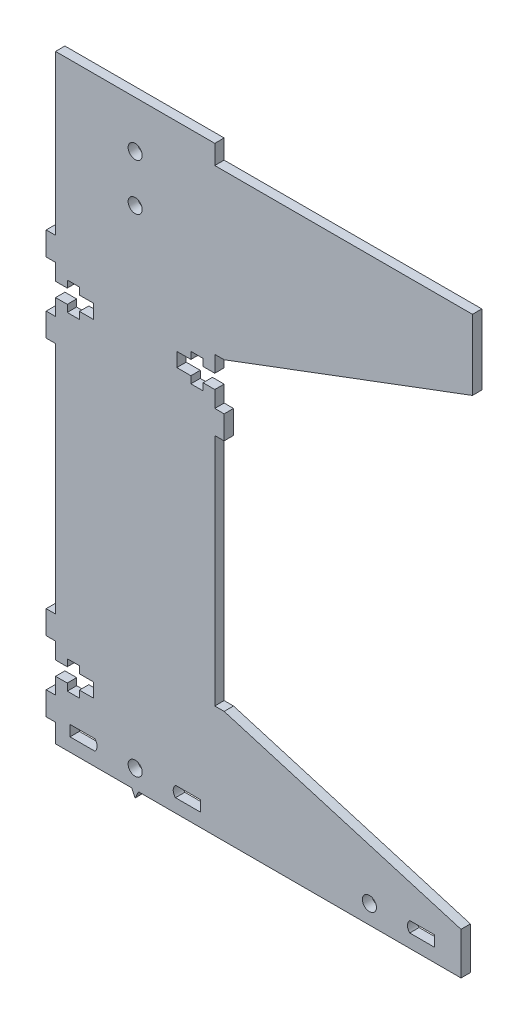
SolidWorks part; units mm, degrees
ref_plane "前视基准面" through (0, 0, 0) normal (0, 0, 1) x (1, 0, 0)
ref_plane "上视基准面" through (0, 0, 0) normal (0, 1, 0) x (1, 0, 0)
ref_plane "右视基准面" through (0, 0, 0) normal (1, 0, 0) x (0, 0, -1)
sketch "草图1" plane through (0, 0, 0) normal (0, 0, 1) x (1, 0, 0)
  line L26 (13.9, -105.15) -> (8.6, -105.15)
  line L27 (13.9, -102.85) -> (13.9, -105.15)
  line L34 (13.9, -102.85) -> (8.6, -102.85)
  line L35 (16.9939, 15.9) -> (16.9939, 20)
  line L36 (71.9939, 15.9) -> (16.9939, 15.9)
  line L37 (71.9939, 0.9) -> (71.9939, 15.9)
  line L40 (18.9939, -34) -> (16.9939, -34)
  line L41 (18.9939, -29) -> (16.9939, -29)
  line L42 (18.9939, -34) -> (18.9939, -29)
  line L47 (16.9939, -22.5) -> (16.9939, -19)
  line L64 (0, -108) -> (0, -109.5)
  line L77 (-13.9, -102.85) -> (-8.6, -102.85)
  line L78 (-13.9, -102.85) -> (-13.9, -105.15)
  line L79 (-13.9, -105.15) -> (-8.6, -105.15)
  line L94 (0, -109.5) -> (0.7212, -108)
  line L95 (0.7212, -108) -> (16.9939, -108)
  line L96 (-0.7212, -108) -> (-16.9939, -108)
  line L97 (0, -109.5) -> (-0.7212, -108)
  line L124 (16.9939, -25.5) -> (16.9939, -29)
  line L126 (14.4939, -25.5) -> (16.9939, -25.5)
  line L127 (14.4939, -21) -> (11.8939, -21)
  line L128 (11.8939, -21) -> (11.8939, -22.5)
  line L129 (11.8939, -22.5) -> (8.8939, -22.5)
  line L130 (11.8939, -25.5) -> (8.8939, -25.5)
  line L131 (11.8939, -27) -> (11.8939, -25.5)
  line L132 (14.4939, -27) -> (11.8939, -27)
  line L133 (16.9939, -22.5) -> (14.4939, -22.5)
  line L134 (14.4939, -22.5) -> (14.4939, -21)
  line L135 (8.8939, -22.5) -> (8.8939, -25.5)
  line L136 (14.4939, -25.5) -> (14.4939, -27)
  line L138 (-18.9939, -104) -> (-18.9939, -99)
  line L139 (-18.9939, -99) -> (-16.9939, -99)
  line L140 (-18.9939, -104) -> (-16.9939, -104)
  line L141 (-14.4939, -95.5) -> (-14.4939, -97)
  line L142 (-8.8939, -92.5) -> (-8.8939, -95.5)
  line L143 (-14.4939, -92.5) -> (-14.4939, -91)
  line L144 (-16.9939, -92.5) -> (-14.4939, -92.5)
  line L145 (-14.4939, -97) -> (-11.8939, -97)
  line L146 (-11.8939, -97) -> (-11.8939, -95.5)
  line L147 (-11.8939, -95.5) -> (-8.8939, -95.5)
  line L148 (-11.8939, -92.5) -> (-8.8939, -92.5)
  line L149 (-11.8939, -91) -> (-11.8939, -92.5)
  line L150 (-14.4939, -91) -> (-11.8939, -91)
  line L151 (-14.4939, -95.5) -> (-16.9939, -95.5)
  line L152 (-16.9939, -89) -> (-16.9939, -92.5)
  line L153 (-16.9939, -95.5) -> (-16.9939, -99)
  line L154 (-16.9939, -89) -> (-18.9939, -89)
  line L155 (-18.9939, -89) -> (-18.9939, -84)
  line L156 (-18.9939, -84) -> (-16.9939, -84)
  line L158 (-16.9939, -104) -> (-16.9939, -108)
  line L179 (-14.4939, -25.5) -> (-14.4939, -27)
  line L180 (-8.8939, -22.5) -> (-8.8939, -25.5)
  line L181 (-14.4939, -22.5) -> (-14.4939, -21)
  line L182 (-16.9939, -22.5) -> (-14.4939, -22.5)
  line L183 (-14.4939, -27) -> (-11.8939, -27)
  line L184 (-11.8939, -27) -> (-11.8939, -25.5)
  line L185 (-11.8939, -25.5) -> (-8.8939, -25.5)
  line L186 (-11.8939, -22.5) -> (-8.8939, -22.5)
  line L187 (-11.8939, -21) -> (-11.8939, -22.5)
  line L188 (-14.4939, -21) -> (-11.8939, -21)
  line L189 (-14.4939, -25.5) -> (-16.9939, -25.5)
  line L190 (-16.9939, -25.5) -> (-16.9939, -29)
  line L191 (-16.9939, -22.5) -> (-16.9939, -19)
  line L192 (-18.9939, -34) -> (-18.9939, -29)
  line L193 (-18.9939, -29) -> (-16.9939, -29)
  line L194 (-18.9939, -34) -> (-16.9939, -34)
  line L195 (-16.9939, -34) -> (-16.9939, -84)
  line L199 (-18.9939, -19) -> (-16.9939, -19)
  line L200 (-16.9939, 15.9) -> (-16.9939, 20)
  line L201 (-16.9939, 20) -> (16.9939, 20)
  line L207 (16.9939, -84) -> (16.9939, -34)
  line L208 (69.5539, -105) -> (69.5539, -99)
  line L210 (-18.9939, -19) -> (-18.9939, -14)
  line L211 (-18.9939, -14) -> (-16.9939, -14)
  line L212 (-16.9939, -14) -> (-16.9939, 15.9)
  line L213 (16.9939, -19) -> (18.9939, -19)
  line L215 (16.9939, -84) -> (18.9939, -84)
  line L216 (18.9939, -84) -> (69.5539, -99)
  line L217 (16.9939, -108) -> (69.5539, -108)
  line L218 (69.5539, -108) -> (69.5539, -105)
  line L219 (63.9, -105.15) -> (58.6, -105.15)
  line L220 (63.9, -102.85) -> (63.9, -105.15)
  line L221 (63.9, -102.85) -> (58.6, -102.85)
  line L222 (9.75, -104) -> (59.75, -104) construction
  line L223 (18.9939, -19) -> (71.9939, 0.9)
  circle A4 centre (0, -104) radius 1.5
  circle A6 centre (0, 0) radius 1.5
  circle A7 centre (0, 10) radius 1.5
  arc A8 (-8.6, -102.85) -> (-8.6, -105.15) centre (-9.75, -104) cw
  arc A9 (8.6, -102.85) -> (8.6, -105.15) centre (9.75, -104) ccw
  circle A10 centre (50, -104) radius 1.5
  arc A11 (58.6, -102.85) -> (58.6, -105.15) centre (59.75, -104) ccw
extrude "凸台-拉伸1" add sketch "草图1" along normal blind 2
sketch "草图7" plane through (-16.9939, 0, 0) normal (-1, 0, 0) x (0, 0, 1)
  line L0 (1, -92.5) -> (1, -95.5)
  line L1 (2, -92.5) -> (0, -92.5) construction
  line L2 (2, -95.5) -> (0, -95.5) construction
  circle A0 centre (1, -94) radius 1.5
sketch "草图8" plane through (16.9939, 0, 0) normal (1, 0, 0) x (0, 0, -1)
  line L0 (-1, -22.5) -> (-1, -25.5) construction
  line L1 (-2, -22.5) -> (0, -22.5) construction
  line L2 (-2, -25.5) -> (0, -25.5) construction
  circle A0 centre (-1, -24) radius 1.5
sketch "草图6" plane through (-16.9939, 0, 0) normal (-1, 0, 0) x (0, 0, 1)
  line L0 (1, -92.5) -> (1, -95.5)
  line L1 (2, -92.5) -> (0, -92.5) construction
  line L2 (2, -95.5) -> (0, -95.5) construction
  circle A0 centre (1, -94) radius 1.5
